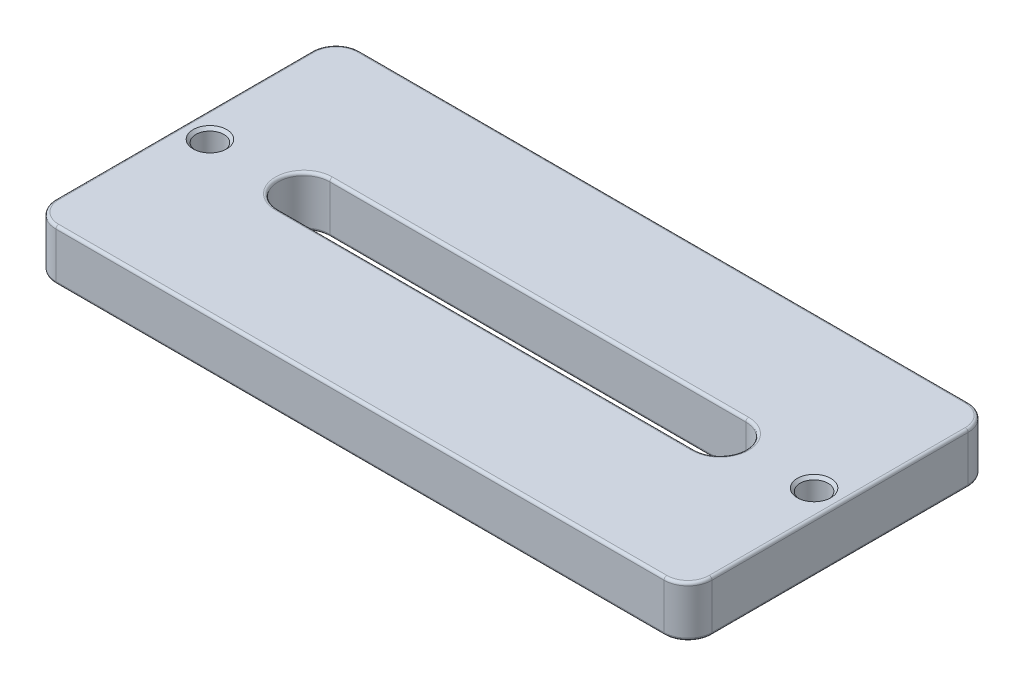
SolidWorks part; units mm, degrees
ref_plane "Front" through (0, 0, 0) normal (0, 0, 1) x (1, 0, 0)
ref_plane "Top" through (0, 0, 0) normal (0, 1, 0) x (1, 0, 0)
ref_plane "Right" through (0, 0, 0) normal (1, 0, 0) x (0, 0, -1)
sketch "Sketch1" plane through (0, 0, 0) normal (0, 1, 0) x (1, 0, 0)
  line L0 (0, 4.8014) -> (0, -3.1451) construction
  line L1 (-41, 19) -> (41, 19)
  line L3 (-41, -19) -> (41, -19)
  line L5 (-4.3063, 0) -> (6.6584, 0) construction
  line L6 (-25.9975, 3.225) -> (-13.6235, 3.225)
  line L7 (-25.9975, -3.225) -> (-13.6235, -3.225)
  line L8 (13.6235, 3.225) -> (25.9975, 3.225)
  line L9 (13.6235, -3.225) -> (25.9975, -3.225)
  line L18 (41, 19) -> (41, -19)
  line L19 (-41, -19) -> (-41, 19)
  line L20 (-13.6235, 3.225) -> (13.6235, 3.225)
  line L21 (-13.6235, -3.225) -> (13.6235, -3.225)
  arc A1 (25.9975, -3.225) -> (25.9975, 3.225) centre (25.9975, 0) ccw
  arc A2 (-25.9975, 3.225) -> (-25.9975, -3.225) centre (-25.9975, 0) ccw
  circle A10 centre (28, -12.5) radius 1.75 construction
  circle A11 centre (28, 12.5) radius 1.75 construction
  circle A12 centre (-28, 12.5) radius 1.75 construction
  circle A13 centre (-28, -12.5) radius 1.75 construction
  circle A14 centre (37.75, 0) radius 1.75
  circle A15 centre (-37.75, 0) radius 1.75
  circle A16 centre (0, 0) radius 6.3672 construction
  point P10 (0, 14)
  point P12 (-29.2225, 0)
  dimension "D4" = 6.45
  dimension "D5" = 3.5
  dimension "D11" = 3.5
  dimension "D6" = 3.5
  dimension "D1" = 82
  dimension "D2" = 38
  dimension "D7" = 3.25
  dimension "D8" = 55.22
  dimension "D12" = 13
  dimension "D13" = 6.5
extrude "Boss-Extrude1" add sketch "Sketch1" along normal blind 6.35
fillet "Fillet2" radius 3 4 edges at (41, 3.175, -19) (41, 3.175, 19) (-41, 3.175, -19) (-41, 3.175, 19)
fillet "Fillet3" radius 0.35 24 edges at (29.2225, 6.35, 0) (0, 6.35, 3.225) (-29.2225, 6.35, 0) (29.2225, 0, 0) (0, 0, 3.225) (-29.2225, 0, 0) (0, 6.35, -3.225) (0, 0, -3.225) (40.1213, 0, -18.1213) (41, 0, 0) (40.1213, 0, 18.1213) (0, 0, 19) (-40.1213, 0, 18.1213) (-41, 0, 0) (-40.1213, 0, -18.1213) (40.1213, 6.35, -18.1213) (41, 6.35, 0) (40.1213, 6.35, 18.1213) (0, 6.35, 19) (-40.1213, 6.35, 18.1213) (-41, 6.35, 0) (-40.1213, 6.35, -18.1213) (0, 0, -19) (0, 6.35, -19)
chamfer "Chamfer1" distance 0.35 angle 45 4 edges at (-37.75, 0, 1.75) (-37.75, 6.35, 1.75) (37.75, 0, 1.75) (37.75, 6.35, 1.75)
